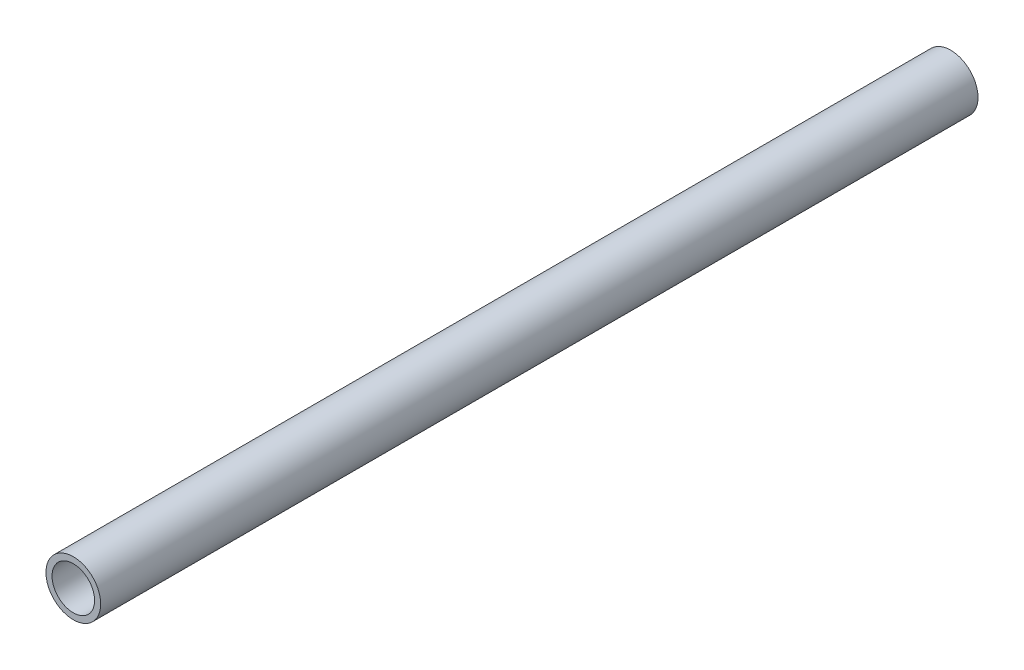
SolidWorks part; units mm, degrees
ref_plane "Front Plane" through (0, 0, 0) normal (0, 0, 1) x (1, 0, 0)
ref_plane "Top Plane" through (0, 0, 0) normal (0, 1, 0) x (1, 0, 0)
ref_plane "Right Plane" through (0, 0, 0) normal (1, 0, 0) x (0, 0, -1)
sketch "Sketch1" plane through (0, 0, 0) normal (0, 0, 1) x (1, 0, 0)
  circle A0 centre (0, 0) radius 9
  circle A1 centre (0, 0) radius 7
  dimension "D1" = 14
  dimension "D2" = 18
extrude "Boss-Extrude1" add sketch "Sketch1" along normal blind 288.574
